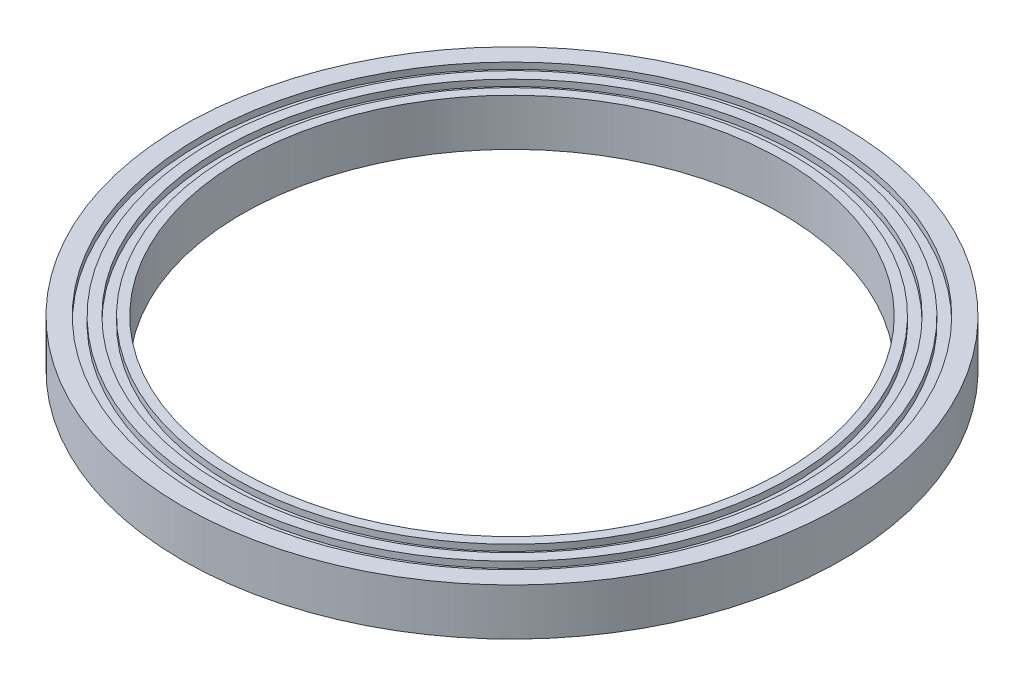
SolidWorks part; units mm, degrees
ref_plane "Front Plane" through (0, 0, 0) normal (0, 0, 1) x (1, 0, 0)
ref_plane "Top Plane" through (0, 0, 0) normal (0, 1, 0) x (1, 0, 0)
ref_plane "Right Plane" through (0, 0, 0) normal (1, 0, 0) x (0, 0, -1)
sketch "Sketch1" plane through (0, 0, 0) normal (0, 1, 0) x (1, 0, 0)
  circle A0 centre (0, 0) radius 8945
  circle A1 centre (0, 0) radius 9945
  dimension "17" = 17890
  dimension "D2" = 19890
extrude "Boss-Extrude1" add sketch "Sketch1" along normal blind 600
sketch "Sketch2" plane through (0, 0, 0) normal (0, 1, 0) x (1, 0, 0)
  circle A0 centre (0, 0) radius 10540
  circle A1 centre (0, 0) radius 8945
extrude "Boss-Extrude2" add sketch "Sketch2" along normal blind 1500
sketch "Sketch3" plane through (0, 0, 0) normal (0, -1, 0) x (1, 0, 0)
  circle A0 centre (0, 0) radius 9945
  circle A1 centre (0, 0) radius 8945
extrude "Cut-Extrude1" cut sketch "Sketch3" against normal blind 500
sketch "Sketch4" plane through (0, 0, 0) normal (0, 1, 0) x (1, 0, 0)
  circle A0 centre (0, 0) radius 8645
  circle A1 centre (0, 0) radius 8945
extrude "Boss-Extrude3" add sketch "Sketch4" along normal blind 1500
sketch "Sketch5" plane through (0, 1500, 0) normal (0, 1, 0) x (1, 0, 0)
  circle A0 centre (0, 0) radius 8945
  circle A1 centre (0, 0) radius 9275
extrude "Cut-Extrude2" cut sketch "Sketch5" against normal blind 200
sketch "Sketch6" plane through (0, 1500, 0) normal (0, 1, 0) x (1, 0, 0)
  circle A0 centre (0, 0) radius 9610
  circle A1 centre (0, 0) radius 9945
extrude "Cut-Extrude3" cut sketch "Sketch6" against normal blind 200
